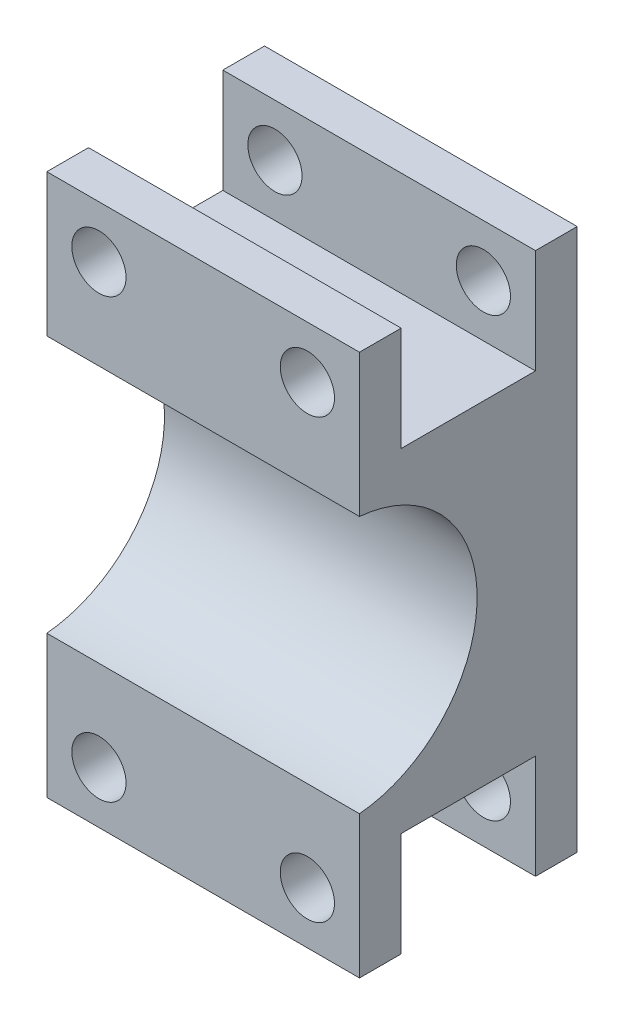
SolidWorks part; units mm, degrees
material "ABS"
ref_plane "Спереди" through (0, 0, 0) normal (0, 0, 1) x (1, 0, 0)
ref_plane "Сверху" through (0, 0, 0) normal (0, 1, 0) x (1, 0, 0)
ref_plane "Справа" through (0, 0, 0) normal (1, 0, 0) x (0, 0, -1)
sketch "Эскиз1" plane through (0, 0, 0) normal (0, 0, 1) x (1, 0, 0)
  line L0 (0, 0) -> (30, 0)
  line L1 (30, 0) -> (30, 32)
  line L2 (30, 32) -> (0, 32)
  line L3 (0, 32) -> (0, 0)
  dimension "D1" = 30
  dimension "D2" = 32
extrude "Бобышка-Вытянуть1" add sketch "Эскиз1" along normal blind 7
ref_plane "Плоскость5" through (0, 0, 0) normal (-1, 0, 0) x (0, 0, 1)
sketch "Эскиз2" plane through (0, 0, 0) normal (-1, 0, 0) x (0, 0, 1)
  line L0 (7, 32) -> (20.8876, 32)
  line L1 (20.8876, 0) -> (7, 0)
  line L2 (7, 0) -> (7, 32)
  line L3 (20.8876, 32) -> (20.8876, 28.35)
  line L4 (20.8876, 3.65) -> (20.8876, 0)
  arc A2 (20.8876, 28.35) -> (20.8876, 3.65) centre (22, 16) ccw
  dimension "D1" = 12.4
  dimension "D3" = 3.65
  dimension "D2" = 16
  dimension "D4" = 3.65
  dimension "D5" = 15
extrude "Бобышка-Вытянуть2" add sketch "Эскиз2" against normal blind 30
sketch "Эскиз3" plane through (0, 0, 0) normal (0, 0, -1) x (-1, 0, 0)
  line L0 (-30, 16) -> (-30, -10)
  line L1 (-30, 0) -> (-30, 32) construction
  line L2 (-30, -10) -> (0, -10)
  line L3 (0, -10) -> (0, 42)
  line L4 (0, -13.695) -> (0, 13.695) construction
  line L5 (0, 42) -> (-30, 42)
  line L6 (-30, 42) -> (-30, 16)
  line L7 (-30, 37) -> (0, 37) construction
  line L8 (-30, -5) -> (0, -5) construction
  circle A0 centre (-25, 37) radius 2.6
  circle A1 centre (-5, 37) radius 2.6
  circle A2 centre (-5, -5) radius 2.6
  circle A3 centre (-25, -5) radius 2.6
  point P16 (-25, 37)
  point P17 (-5, 37)
  point P18 (-5, -5)
  point P19 (-25, -5)
  dimension "D7" = 5.2
  dimension "D9" = 5.2
  dimension "D10" = 5
  dimension "D12" = 5.2
  dimension "D13" = 5.2
  dimension "D1" = 10
  dimension "D2" = 10
  dimension "D3" = 30
  dimension "D4" = 5
  dimension "D5" = 5
  dimension "D6" = 5
  dimension "D8" = 5
  dimension "D11" = 5
extrude "Бобышка-Вытянуть3" add sketch "Эскиз3" against normal blind 4
sketch "Эскиз4" plane through (0, 32, 0) normal (0, 1, 0) x (1, 0, 0)
  line L0 (0, -16.8876) -> (30, -16.8876)
  line L1 (0, -20.8876) -> (0, -4) construction
  line L2 (30, -20.8876) -> (30, -4) construction
  line L3 (30, -20.8876) -> (0, -20.8876) construction
  line L4 (30, -16.8876) -> (30, -20.8876)
  line L5 (30, -20.8876) -> (0, -20.8876)
  line L6 (0, -20.8876) -> (0, -16.8876)
  dimension "D1" = 4
extrude "Бобышка-Вытянуть5" add sketch "Эскиз4" along normal blind 10
sketch "Эскиз5" plane through (0, 0, 0) normal (0, -1, 0) x (1, 0, 0)
  line L0 (30, 20.8876) -> (30, 4) construction
  line L1 (0, 20.8876) -> (30, 20.8876)
  line L2 (0, 20.8876) -> (0, 16.8876)
  line L3 (0, 16.8876) -> (30, 16.8876)
  line L4 (30, 20.8876) -> (30, 16.8876)
  dimension "D1" = 4
extrude "Бобышка-Вытянуть6" add sketch "Эскиз5" along normal blind 10
sketch "Эскиз6" plane through (0, 0, 20.8876) normal (0, 0, 1) x (1, 0, 0)
  line L0 (30, -10) -> (0, -10) construction
  line L2 (30, -10) -> (30, 3.65) construction
  line L3 (0, 42) -> (30, 42) construction
  line L5 (0, 28.35) -> (0, 42) construction
  line L7 (0, -10) -> (0, 3.65) construction
  line L9 (30, 28.35) -> (30, 42) construction
  circle A0 centre (5, 37) radius 2.6
  circle A1 centre (25, 37) radius 2.6
  circle A2 centre (25, -5) radius 2.6
  circle A3 centre (5, -5) radius 2.6
  dimension "D9" = 5.2
  dimension "D10" = 5.2
  dimension "D11" = 5.2
  dimension "D12" = 5.2
  dimension "D1" = 5
  dimension "D2" = 5
  dimension "D3" = 5
  dimension "D4" = 5
  dimension "D5" = 5
  dimension "D6" = 5
  dimension "D7" = 5
  dimension "D8" = 5
extrude "Вырез-Вытянуть1" cut sketch "Эскиз6" against normal blind 10
